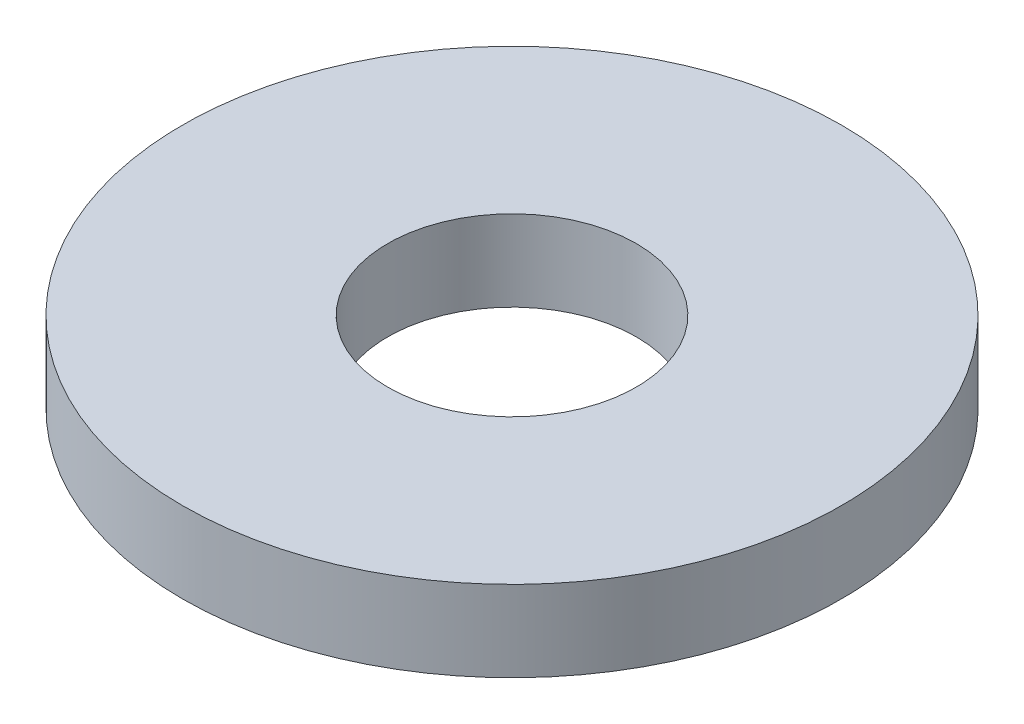
SolidWorks part; units mm, degrees
ref_plane "Front Plane" through (0, 0, 0) normal (0, 0, 1) x (1, 0, 0)
ref_plane "Top Plane" through (0, 0, 0) normal (0, 1, 0) x (1, 0, 0)
ref_plane "Right Plane" through (0, 0, 0) normal (1, 0, 0) x (0, 0, -1)
sketch "Sketch2" plane through (0, 0, 0) normal (0, 1, 0) x (1, 0, 0)
  circle A0 centre (0, 0) radius 13.25
  circle A1 centre (0, 0) radius 5
  dimension "D1" = 26.5
  dimension "D2" = 10
extrude "Boss-Extrude1" add sketch "Sketch2" along normal blind 3.25
